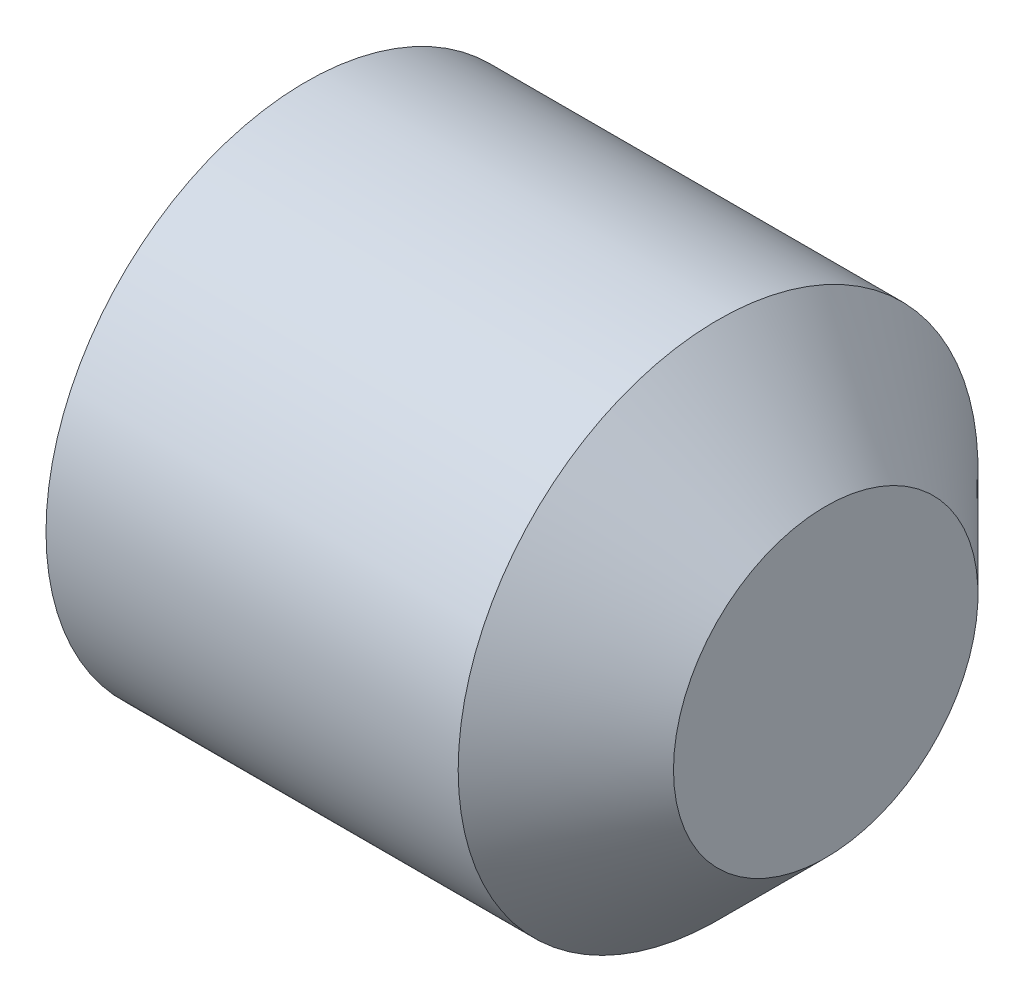
SolidWorks part; units mm, degrees
material "AISI 304"
ref_plane "Front Plane" through (0, 0, 0) normal (0, 0, 1) x (1, 0, 0)
ref_plane "Top Plane" through (0, 0, 0) normal (0, 1, 0) x (1, 0, 0)
ref_plane "Right Plane" through (0, 0, 0) normal (1, 0, 0) x (0, 0, -1)
sketch "Sketch1" plane through (0, 0, 0) normal (0, 0, 1) x (1, 0, 0)
  line L0 (0, 0) -> (105.4919, 0) construction
  line L1 (6, 1.7574) -> (6, 0)
  line L2 (6, 1.7574) -> (4.7574, 3)
  line L3 (4.7574, 3) -> (0, 3)
  line L4 (0, 3) -> (0, 0)
  line L5 (0, 0) -> (6, 0)
  dimension "D1" = 6
  dimension "D2" = 6
  dimension "D3" = 45
  dimension "D4" = 90
revolve "Revolve1" add sketch "Sketch1" angle 360 about L0
sketch "Sketch2" plane through (0, 0, 0) normal (-1, 0, 0) x (0, 0, 1)
  line L1 (-0.866, 1.5) -> (-1.7321, 0)
  line L2 (-1.7321, 0) -> (-0.866, -1.5)
  line L3 (-0.866, -1.5) -> (0.866, -1.5)
  line L4 (0.866, -1.5) -> (1.7321, 0)
  line L5 (1.7321, 0) -> (0.866, 1.5)
  line L6 (0.866, 1.5) -> (-0.866, 1.5)
  circle A0 centre (0, 0) radius 1.5 construction
  dimension "D1" = 3
extrude "Cut-Extrude1" cut sketch "Sketch2" against normal blind 2
